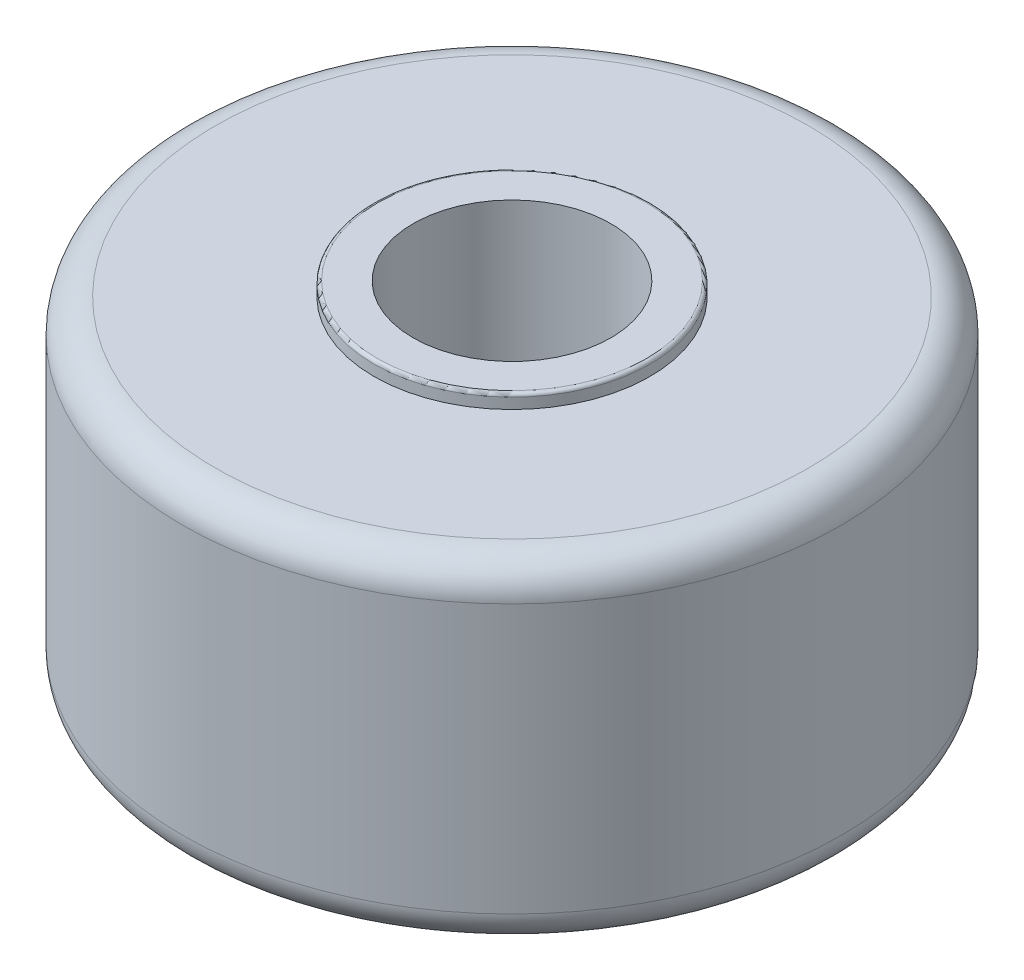
SolidWorks part; units mm, degrees
material "6061-T6 (SS)"
ref_plane "Front Plane" through (0, 0, 0) normal (0, 0, 1) x (1, 0, 0)
ref_plane "Top Plane" through (0, 0, 0) normal (0, 1, 0) x (1, 0, 0)
ref_plane "Right Plane" through (0, 0, 0) normal (1, 0, 0) x (0, 0, -1)
sketch "Sketch1" plane through (0, 0, 0) normal (1, 0, 0) x (0, 0, -1)
  line L0 (0, 25.781) -> (0, -25.781) construction
  line L1 (21.2725, -25.781) -> (21.2725, -27.94)
  line L2 (21.2725, 25.781) -> (50.8, 25.781)
  line L3 (15.2527, 27.94) -> (15.2527, -27.94)
  line L4 (21.2725, -25.781) -> (50.8, -25.781)
  line L5 (50.8, 25.781) -> (50.8, -25.781)
  line L6 (21.2725, -27.94) -> (15.2527, -27.94)
  line L7 (21.2725, 25.781) -> (21.2725, 27.94)
  line L8 (21.2725, 27.94) -> (15.2527, 27.94)
  dimension "D1" = 101.6
  dimension "D2" = 30.5054
  dimension "D3" = 51.562
  dimension "D4" = 55.88
  dimension "D5" = 42.545
revolve "Revolve1" add sketch "Sketch1" angle 360 about L0
fillet "Fillet1" radius 5.08 2 edges at (0, -25.781, 50.8) (0, 25.781, 50.8)
fillet "Fillet2" radius 0.508 2 edges at (0, -27.94, 21.2725) (0, 27.94, 21.2725)
